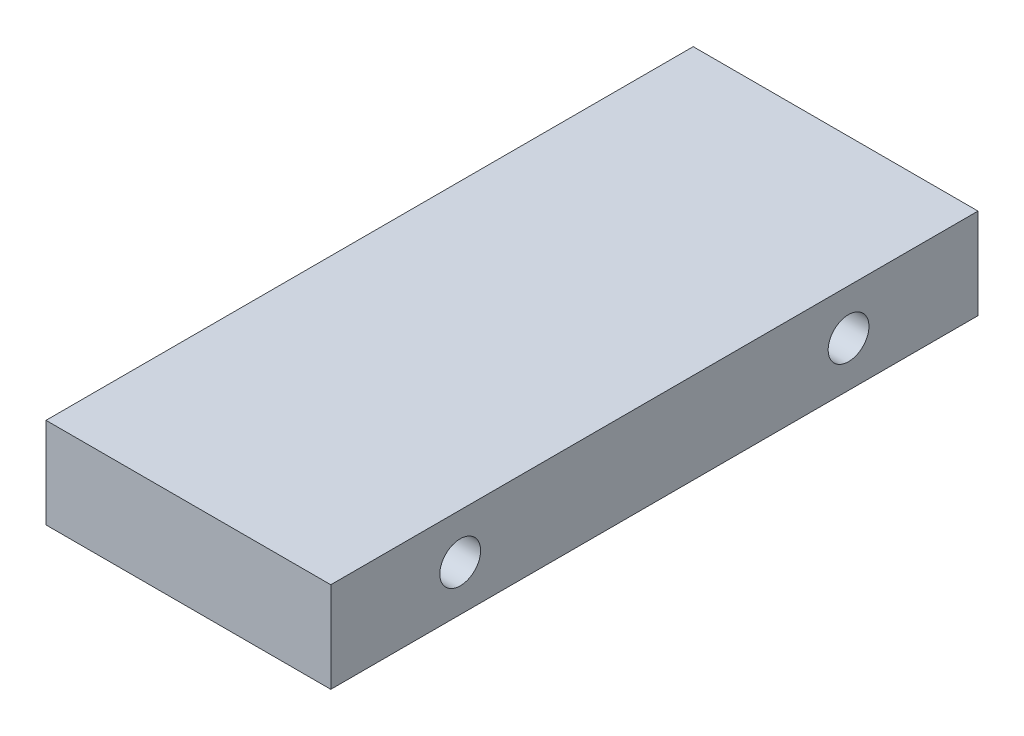
SolidWorks part; units mm, degrees
material "3.0205 (EN-AW 1200)"
ref_plane "Front" through (0, 0, 0) normal (0, 0, 1) x (1, 0, 0)
ref_plane "Top" through (0, 0, 0) normal (0, 1, 0) x (1, 0, 0)
ref_plane "Right" through (0, 0, 0) normal (1, 0, 0) x (0, 0, -1)
sketch "Эскиз1" plane through (0, 0, 0) normal (1, 0, 0) x (0, 0, -1)
  line L1 (-45.2762, 3.6436) -> (4.7238, 3.6436)
  line L2 (-45.2762, 3.6436) -> (-45.2762, -3.3564)
  line L3 (-45.2762, -3.3564) -> (4.7238, -3.3564)
  line L4 (4.7238, 3.6436) -> (4.7238, -3.3564)
  dimension "D1" = 7
  dimension "D2" = 50
extrude "Бобышка-Вытянуть1" add sketch "Эскиз1" along normal blind 22
hole_wizard "Сверло под метчик  спиральное M31" positions "Эскиз3" profile "Эскиз4" hole size "M3x0.5" standard "Ansi Metric"
sketch "Эскиз3" plane through (22, 0, 0) normal (1, 0, 0) x (0, 0, -1)
  line L0 (-45.2762, -3.3564) -> (4.7238, -3.3564) construction
  line L1 (-45.2762, 3.6436) -> (-45.2762, -3.3564) construction
  line L2 (4.7238, -3.3564) -> (4.7238, 3.6436) construction
  point P0 (-35.2762, 0.1436)
  point P2 (-5.2762, 0.1436)
  dimension "D1" = 3.5
  dimension "D2" = 10
  dimension "D3" = 10
sketch "Эскиз4" plane through (22, 0.1436, 35.2762) normal (0, 1, 0) x (0, 0, -1)
  line L0 (0, 0) -> (0, 10.9464)
  line L1 (0, 10.9464) -> (1.575, 10)
  line L2 (1.575, 10) -> (1.575, 0)
  line L5 (1.575, 0) -> (0, 0)
  line L10 (0, 10.9464) -> (-1.575, 10) construction
  line L11 (0, -6.35) -> (0, 107.95) construction
  dimension "Диаметр отверстия" = 3.15
  dimension "Глубина отверстия" = 10
  dimension "Угол заточки сверла" = 118
hole_wizard "Сверло под метчик  спиральное M32" positions "Эскиз6" profile "Эскиз5" hole size "M3x0.5" standard "Ansi Metric"
sketch "Эскиз6" plane through (0, 0, 0) normal (-1, 0, 0) x (0, 0, 1)
  line L0 (45.2762, -3.3564) -> (-4.7238, -3.3564) construction
  line L1 (45.2762, 3.6436) -> (45.2762, -3.3564) construction
  point P0 (20.2762, 0.1436)
  dimension "D1" = 3.5
  dimension "D2" = 25
sketch "Эскиз5" plane through (0, 0.1436, 20.2762) normal (0, 1, 0) x (0, 0, 1)
  line L0 (0, 0) -> (0, 10.9464)
  line L1 (0, 10.9464) -> (1.575, 10)
  line L2 (1.575, 10) -> (1.575, 0)
  line L5 (1.575, 0) -> (0, 0)
  line L10 (0, 10.9464) -> (-1.575, 10) construction
  line L11 (0, -6.35) -> (0, 107.95) construction
  dimension "Диаметр отверстия" = 3.15
  dimension "Глубина отверстия" = 10
  dimension "Угол заточки сверла" = 118
